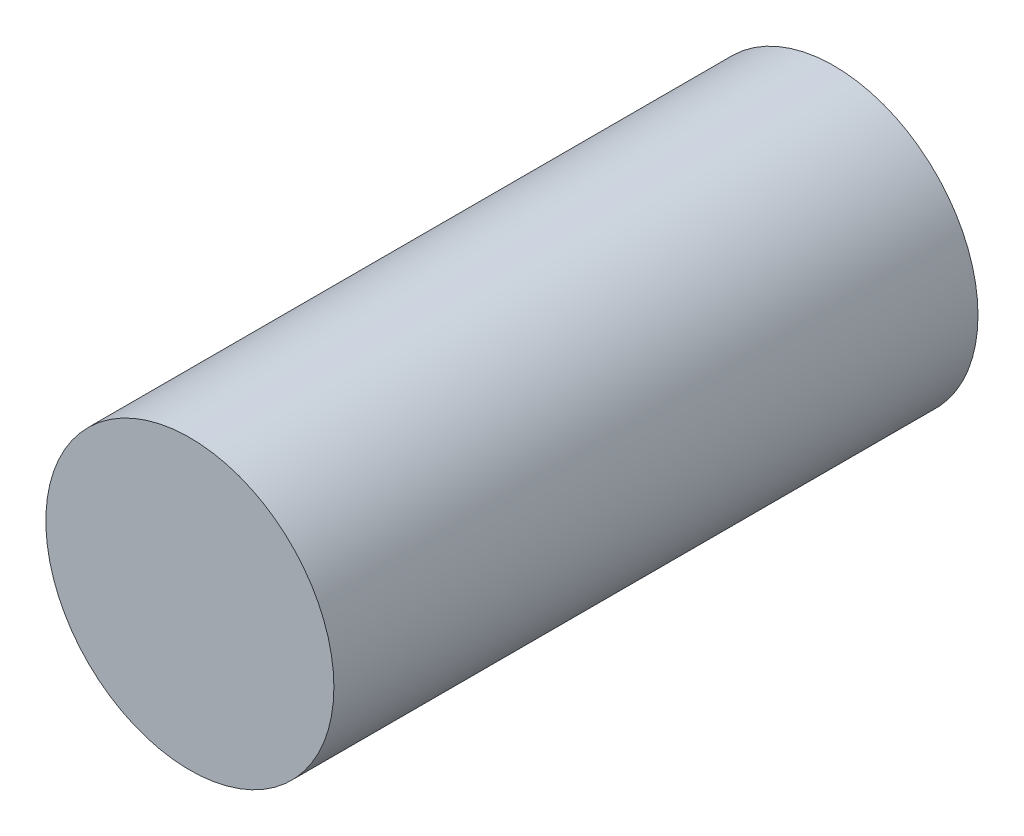
SolidWorks part; units mm, degrees
ref_plane "Front Plane" through (0, 0, 0) normal (0, 0, 1) x (1, 0, 0)
ref_plane "Top Plane" through (0, 0, 0) normal (0, 1, 0) x (1, 0, 0)
ref_plane "Right Plane" through (0, 0, 0) normal (1, 0, 0) x (0, 0, -1)
sketch "Sketch1" plane through (0, 0, 0) normal (0, 0, 1) x (1, 0, 0)
  circle A0 centre (0, 0) radius 18
  dimension "D1" = 36
extrude "Boss-Extrude1" add sketch "Sketch1" along normal blind 80.5
sketch "Sketch3" plane through (0, 0, 0) normal (0, 0, -1) x (-1, 0, 0)
  circle A0 centre (0, -8.7671) radius 6
  dimension "D1" = 12
extrude "Boss-Extrude2" add sketch "Sketch3" along normal blind 6.8
